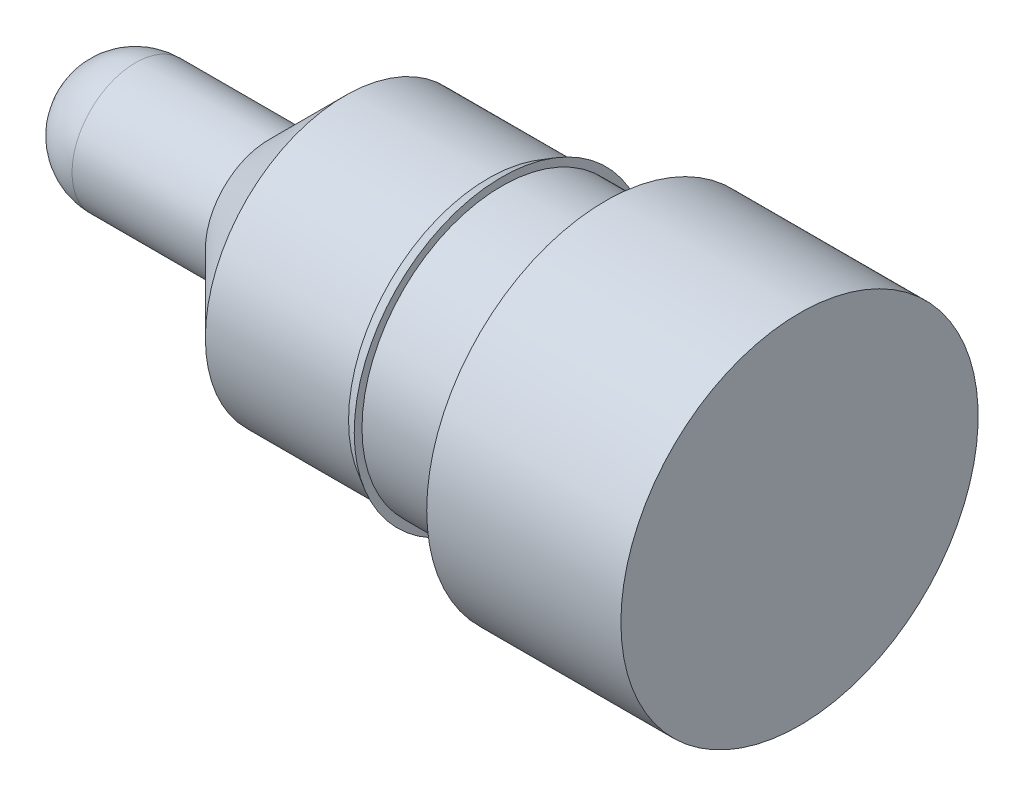
SolidWorks part; units mm, degrees
ref_plane "Front Plane" through (0, 0, 0) normal (0, 0, 1) x (1, 0, 0)
ref_plane "Top Plane" through (0, 0, 0) normal (0, 1, 0) x (1, 0, 0)
ref_plane "Right Plane" through (0, 0, 0) normal (1, 0, 0) x (0, 0, -1)
sketch "Sketch1" plane through (0, 0, 0) normal (0, 0, 1) x (1, 0, 0)
  line L0 (-2.1737, 0) -> (10.5263, 0) construction
  line L1 (0, 0) -> (0, 0.6223)
  line L2 (0, 0.6223) -> (1.9304, 0.6223)
  line L3 (1.9304, 0.6223) -> (2.6797, 1.3716)
  line L4 (2.6797, 1.3716) -> (4.0844, 1.3716)
  line L5 (4.0844, 1.3716) -> (4.2164, 1.4478)
  line L6 (4.2164, 1.4478) -> (4.2164, 1.3716)
  line L7 (4.2164, 1.3716) -> (5.2324, 1.3716)
  line L8 (5.2324, 1.3716) -> (5.2324, 1.7526)
  line L9 (5.2324, 1.7526) -> (7.1374, 1.7526)
  line L10 (7.1374, 1.7526) -> (7.1374, 0)
  line L11 (7.1374, 0) -> (0, 0)
  dimension "D1" = 30
  dimension "D2" = 45
  dimension "D3" = 1.2446
  dimension "D4" = 2.7432
  dimension "D5" = 3.5052
  dimension "D6" = 1.9304
  dimension "D7" = 2.8956
  dimension "D8" = 1.016
  dimension "D9" = 7.1374
  dimension "D10" = 1.905
revolve "Revolve1" add sketch "Sketch1" angle 360 about L0
sketch "Sketch2" plane through (0, 0, 0) normal (0, 0, 1) x (1, 0, 0)
  line L0 (-2.1737, 0) -> (10.5263, 0) construction
  line L1 (0, 0.6223) -> (0, -0.6223) construction
  line L2 (1.9304, 0.6223) -> (0, 0.6223) construction
  line L3 (0.6223, 0.6223) -> (-0.2377, 0.6223)
  line L4 (-0.2377, 0.6223) -> (-0.2377, 0)
  line L5 (-0.2377, 0) -> (0, 0)
  arc A0 (0.6223, 0.6223) -> (0, 0) centre (0.6223, 0) ccw
  dimension "D1" = 0.2377
revolve "Cut-Revolve1" cut sketch "Sketch2" angle 360 about axis through (-2.1737, 0, 0) along (1, 0, 0)
